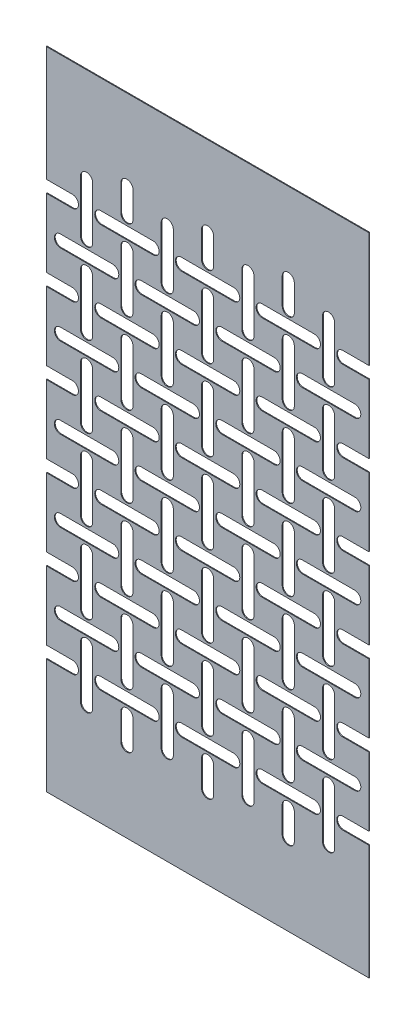
SolidWorks part; units mm, degrees
material "Kapton"
ref_plane "Front Plane" through (0, 0, 0) normal (0, 0, 1) x (1, 0, 0)
ref_plane "Top Plane" through (0, 0, 0) normal (0, 1, 0) x (1, 0, 0)
ref_plane "Right Plane" through (0, 0, 0) normal (1, 0, 0) x (0, 0, -1)
sketch "Model" plane through (0, 0, 0) normal (0, 0, 1) x (1, 0, 0)
  line L0 (0, 31.5) -> (6.4793, 31.5)
  line L1 (0, 28.5) -> (6.4793, 28.5)
  line L2 (13.5207, 31.5) -> (26.4793, 31.5)
  line L3 (13.5207, 28.5) -> (26.4793, 28.5)
  line L4 (33.5207, 31.5) -> (46.4793, 31.5)
  line L5 (33.5207, 28.5) -> (46.4793, 28.5)
  line L6 (53.5207, 31.5) -> (66.4793, 31.5)
  line L7 (53.5207, 28.5) -> (66.4793, 28.5)
  line L8 (73.5207, 31.5) -> (80, 31.5)
  line L9 (73.5207, 28.5) -> (80, 28.5)
  line L10 (3.5207, 41.5) -> (16.4793, 41.5)
  line L11 (3.5207, 38.5) -> (16.4793, 38.5)
  line L12 (23.5207, 41.5) -> (36.4793, 41.5)
  line L13 (23.5207, 38.5) -> (36.4793, 38.5)
  line L14 (43.5207, 41.5) -> (56.4793, 41.5)
  line L15 (43.5207, 38.5) -> (56.4793, 38.5)
  line L16 (63.5207, 41.5) -> (76.4793, 41.5)
  line L17 (63.5207, 38.5) -> (76.4793, 38.5)
  line L18 (0, 51.5) -> (6.4793, 51.5)
  line L19 (0, 48.5) -> (6.4793, 48.5)
  line L20 (13.5207, 51.5) -> (26.4793, 51.5)
  line L21 (13.5207, 48.5) -> (26.4793, 48.5)
  line L22 (33.5207, 51.5) -> (46.4793, 51.5)
  line L23 (33.5207, 48.5) -> (46.4793, 48.5)
  line L24 (53.5207, 51.5) -> (66.4793, 51.5)
  line L25 (53.5207, 48.5) -> (66.4793, 48.5)
  line L26 (73.5207, 51.5) -> (80, 51.5)
  line L27 (73.5207, 48.5) -> (80, 48.5)
  line L28 (3.5207, 61.5) -> (16.4793, 61.5)
  line L29 (3.5207, 58.5) -> (16.4793, 58.5)
  line L30 (23.5207, 61.5) -> (36.4793, 61.5)
  line L31 (23.5207, 58.5) -> (36.4793, 58.5)
  line L32 (43.5207, 61.5) -> (56.4793, 61.5)
  line L33 (43.5207, 58.5) -> (56.4793, 58.5)
  line L34 (63.5207, 61.5) -> (76.4793, 61.5)
  line L35 (63.5207, 58.5) -> (76.4793, 58.5)
  line L36 (0, 71.5) -> (6.4793, 71.5)
  line L37 (0, 68.5) -> (6.4793, 68.5)
  line L38 (13.5207, 71.5) -> (26.4793, 71.5)
  line L39 (13.5207, 68.5) -> (26.4793, 68.5)
  line L40 (33.5207, 71.5) -> (46.4793, 71.5)
  line L41 (33.5207, 68.5) -> (46.4793, 68.5)
  line L42 (53.5207, 71.5) -> (66.4793, 71.5)
  line L43 (53.5207, 68.5) -> (66.4793, 68.5)
  line L44 (73.5207, 71.5) -> (80, 71.5)
  line L45 (73.5207, 68.5) -> (80, 68.5)
  line L46 (3.5207, 81.5) -> (16.4793, 81.5)
  line L47 (3.5207, 78.5) -> (16.4793, 78.5)
  line L48 (23.5207, 81.5) -> (36.4793, 81.5)
  line L49 (23.5207, 78.5) -> (36.4793, 78.5)
  line L50 (43.5207, 81.5) -> (56.4793, 81.5)
  line L51 (43.5207, 78.5) -> (56.4793, 78.5)
  line L52 (63.5207, 81.5) -> (76.4793, 81.5)
  line L53 (63.5207, 78.5) -> (76.4793, 78.5)
  line L54 (0, 91.5) -> (6.4793, 91.5)
  line L55 (0, 88.5) -> (6.4793, 88.5)
  line L56 (13.5207, 91.5) -> (26.4793, 91.5)
  line L57 (13.5207, 88.5) -> (26.4793, 88.5)
  line L58 (33.5207, 91.5) -> (46.4793, 91.5)
  line L59 (33.5207, 88.5) -> (46.4793, 88.5)
  line L60 (53.5207, 91.5) -> (66.4793, 91.5)
  line L61 (53.5207, 88.5) -> (66.4793, 88.5)
  line L62 (73.5207, 91.5) -> (80, 91.5)
  line L63 (73.5207, 88.5) -> (80, 88.5)
  line L64 (3.5207, 101.5) -> (16.4793, 101.5)
  line L65 (3.5207, 98.5) -> (16.4793, 98.5)
  line L66 (23.5207, 101.5) -> (36.4793, 101.5)
  line L67 (23.5207, 98.5) -> (36.4793, 98.5)
  line L68 (43.5207, 101.5) -> (56.4793, 101.5)
  line L69 (43.5207, 98.5) -> (56.4793, 98.5)
  line L70 (63.5207, 101.5) -> (76.4793, 101.5)
  line L71 (63.5207, 98.5) -> (76.4793, 98.5)
  line L72 (0, 111.5) -> (6.4793, 111.5)
  line L73 (0, 108.5) -> (6.4793, 108.5)
  line L74 (13.5207, 111.5) -> (26.4793, 111.5)
  line L75 (13.5207, 108.5) -> (26.4793, 108.5)
  line L76 (33.5207, 111.5) -> (46.4793, 111.5)
  line L77 (33.5207, 108.5) -> (46.4793, 108.5)
  line L78 (53.5207, 111.5) -> (66.4793, 111.5)
  line L79 (53.5207, 108.5) -> (66.4793, 108.5)
  line L80 (73.5207, 111.5) -> (80, 111.5)
  line L81 (73.5207, 108.5) -> (80, 108.5)
  line L82 (3.5207, 121.5) -> (16.4793, 121.5)
  line L83 (3.5207, 118.5) -> (16.4793, 118.5)
  line L84 (23.5207, 121.5) -> (36.4793, 121.5)
  line L85 (23.5207, 118.5) -> (36.4793, 118.5)
  line L86 (43.5207, 121.5) -> (56.4793, 121.5)
  line L87 (43.5207, 118.5) -> (56.4793, 118.5)
  line L88 (63.5207, 121.5) -> (76.4793, 121.5)
  line L89 (63.5207, 118.5) -> (76.4793, 118.5)
  line L90 (0, 131.5) -> (6.4793, 131.5)
  line L91 (0, 128.5) -> (6.4793, 128.5)
  line L92 (13.5207, 131.5) -> (26.4793, 131.5)
  line L93 (13.5207, 128.5) -> (26.4793, 128.5)
  line L94 (33.5207, 131.5) -> (46.4793, 131.5)
  line L95 (33.5207, 128.5) -> (46.4793, 128.5)
  line L96 (53.5207, 131.5) -> (66.4793, 131.5)
  line L97 (53.5207, 128.5) -> (66.4793, 128.5)
  line L98 (73.5207, 131.5) -> (80, 131.5)
  line L99 (73.5207, 128.5) -> (80, 128.5)
  line L100 (11.5, 23.5207) -> (11.5, 36.4793)
  line L101 (8.5, 23.5207) -> (8.5, 36.4793)
  line L102 (11.5, 43.5207) -> (11.5, 56.4793)
  line L103 (8.5, 43.5207) -> (8.5, 56.4793)
  line L104 (11.5, 63.5207) -> (11.5, 76.4793)
  line L105 (8.5, 63.5207) -> (8.5, 76.4793)
  line L106 (11.5, 83.5207) -> (11.5, 96.4793)
  line L107 (8.5, 83.5207) -> (8.5, 96.4793)
  line L108 (11.5, 103.5207) -> (11.5, 116.4793)
  line L109 (8.5, 103.5207) -> (8.5, 116.4793)
  line L110 (11.5, 123.5207) -> (11.5, 136.4793)
  line L111 (8.5, 123.5207) -> (8.5, 136.4793)
  line L112 (21.5, 20) -> (21.5, 26.4793)
  line L113 (18.5, 20) -> (18.5, 26.4793)
  line L114 (21.5, 33.5207) -> (21.5, 46.4793)
  line L115 (18.5, 33.5207) -> (18.5, 46.4793)
  line L116 (21.5, 53.5207) -> (21.5, 66.4793)
  line L117 (18.5, 53.5207) -> (18.5, 66.4793)
  line L118 (21.5, 73.5207) -> (21.5, 86.4793)
  line L119 (18.5, 73.5207) -> (18.5, 86.4793)
  line L120 (21.5, 93.5207) -> (21.5, 106.4793)
  line L121 (18.5, 93.5207) -> (18.5, 106.4793)
  line L122 (21.5, 113.5207) -> (21.5, 126.4793)
  line L123 (18.5, 113.5207) -> (18.5, 126.4793)
  line L124 (21.5, 133.5207) -> (21.5, 140)
  line L125 (18.5, 133.5207) -> (18.5, 140)
  line L126 (31.5, 23.5207) -> (31.5, 36.4793)
  line L127 (28.5, 23.5207) -> (28.5, 36.4793)
  line L128 (31.5, 43.5207) -> (31.5, 56.4793)
  line L129 (28.5, 43.5207) -> (28.5, 56.4793)
  line L130 (31.5, 63.5207) -> (31.5, 76.4793)
  line L131 (28.5, 63.5207) -> (28.5, 76.4793)
  line L132 (31.5, 83.5207) -> (31.5, 96.4793)
  line L133 (28.5, 83.5207) -> (28.5, 96.4793)
  line L134 (31.5, 103.5207) -> (31.5, 116.4793)
  line L135 (28.5, 103.5207) -> (28.5, 116.4793)
  line L136 (31.5, 123.5207) -> (31.5, 136.4793)
  line L137 (28.5, 123.5207) -> (28.5, 136.4793)
  line L138 (41.5, 20) -> (41.5, 26.4793)
  line L139 (38.5, 20) -> (38.5, 26.4793)
  line L140 (41.5, 33.5207) -> (41.5, 46.4793)
  line L141 (38.5, 33.5207) -> (38.5, 46.4793)
  line L142 (41.5, 53.5207) -> (41.5, 66.4793)
  line L143 (38.5, 53.5207) -> (38.5, 66.4793)
  line L144 (41.5, 73.5207) -> (41.5, 86.4793)
  line L145 (38.5, 73.5207) -> (38.5, 86.4793)
  line L146 (41.5, 93.5207) -> (41.5, 106.4793)
  line L147 (38.5, 93.5207) -> (38.5, 106.4793)
  line L148 (41.5, 113.5207) -> (41.5, 126.4793)
  line L149 (38.5, 113.5207) -> (38.5, 126.4793)
  line L150 (41.5, 133.5207) -> (41.5, 140)
  line L151 (38.5, 133.5207) -> (38.5, 140)
  line L152 (51.5, 23.5207) -> (51.5, 36.4793)
  line L153 (48.5, 23.5207) -> (48.5, 36.4793)
  line L154 (51.5, 43.5207) -> (51.5, 56.4793)
  line L155 (48.5, 43.5207) -> (48.5, 56.4793)
  line L156 (51.5, 63.5207) -> (51.5, 76.4793)
  line L157 (48.5, 63.5207) -> (48.5, 76.4793)
  line L158 (51.5, 83.5207) -> (51.5, 96.4793)
  line L159 (48.5, 83.5207) -> (48.5, 96.4793)
  line L160 (51.5, 103.5207) -> (51.5, 116.4793)
  line L161 (48.5, 103.5207) -> (48.5, 116.4793)
  line L162 (51.5, 123.5207) -> (51.5, 136.4793)
  line L163 (48.5, 123.5207) -> (48.5, 136.4793)
  line L164 (61.5, 20) -> (61.5, 26.4793)
  line L165 (58.5, 20) -> (58.5, 26.4793)
  line L166 (61.5, 33.5207) -> (61.5, 46.4793)
  line L167 (58.5, 33.5207) -> (58.5, 46.4793)
  line L168 (61.5, 53.5207) -> (61.5, 66.4793)
  line L169 (58.5, 53.5207) -> (58.5, 66.4793)
  line L170 (61.5, 73.5207) -> (61.5, 86.4793)
  line L171 (58.5, 73.5207) -> (58.5, 86.4793)
  line L172 (61.5, 93.5207) -> (61.5, 106.4793)
  line L173 (58.5, 93.5207) -> (58.5, 106.4793)
  line L174 (61.5, 113.5207) -> (61.5, 126.4793)
  line L175 (58.5, 113.5207) -> (58.5, 126.4793)
  line L176 (61.5, 133.5207) -> (61.5, 140)
  line L177 (58.5, 133.5207) -> (58.5, 140)
  line L178 (71.5, 23.5207) -> (71.5, 36.4793)
  line L179 (68.5, 23.5207) -> (68.5, 36.4793)
  line L180 (71.5, 43.5207) -> (71.5, 56.4793)
  line L181 (68.5, 43.5207) -> (68.5, 56.4793)
  line L182 (71.5, 63.5207) -> (71.5, 76.4793)
  line L183 (68.5, 63.5207) -> (68.5, 76.4793)
  line L184 (71.5, 83.5207) -> (71.5, 96.4793)
  line L185 (68.5, 83.5207) -> (68.5, 96.4793)
  line L186 (71.5, 103.5207) -> (71.5, 116.4793)
  line L187 (68.5, 103.5207) -> (68.5, 116.4793)
  line L188 (71.5, 123.5207) -> (71.5, 136.4793)
  line L189 (68.5, 123.5207) -> (68.5, 136.4793)
  line L190 (0, 0) -> (80, 0)
  line L191 (80, 0) -> (80, 28.5)
  line L192 (80, 31.5) -> (80, 48.5)
  line L193 (80, 51.5) -> (80, 68.5)
  line L194 (80, 71.5) -> (80, 88.5)
  line L195 (80, 91.5) -> (80, 108.5)
  line L196 (80, 111.5) -> (80, 128.5)
  line L197 (80, 131.5) -> (80, 160)
  line L198 (80, 160) -> (0, 160)
  line L199 (0, 0) -> (0, 28.5)
  line L200 (0, 31.5) -> (0, 48.5)
  line L201 (0, 51.5) -> (0, 68.5)
  line L202 (0, 71.5) -> (0, 88.5)
  line L203 (0, 91.5) -> (0, 108.5)
  line L204 (0, 111.5) -> (0, 128.5)
  line L205 (0, 131.5) -> (0, 160)
  arc A0 (6.4793, 28.5) -> (6.4793, 31.5) centre (6.4793, 30) ccw
  arc A1 (13.5207, 31.5) -> (13.5207, 28.5) centre (13.5207, 30) ccw
  arc A2 (26.4793, 28.5) -> (26.4793, 31.5) centre (26.4793, 30) ccw
  arc A3 (33.5207, 31.5) -> (33.5207, 28.5) centre (33.5207, 30) ccw
  arc A4 (46.4793, 28.5) -> (46.4793, 31.5) centre (46.4793, 30) ccw
  arc A5 (53.5207, 31.5) -> (53.5207, 28.5) centre (53.5207, 30) ccw
  arc A6 (66.4793, 28.5) -> (66.4793, 31.5) centre (66.4793, 30) ccw
  arc A7 (73.5207, 31.5) -> (73.5207, 28.5) centre (73.5207, 30) ccw
  arc A8 (3.5207, 41.5) -> (3.5207, 38.5) centre (3.5207, 40) ccw
  arc A9 (16.4793, 38.5) -> (16.4793, 41.5) centre (16.4793, 40) ccw
  arc A10 (23.5207, 41.5) -> (23.5207, 38.5) centre (23.5207, 40) ccw
  arc A11 (36.4793, 38.5) -> (36.4793, 41.5) centre (36.4793, 40) ccw
  arc A12 (43.5207, 41.5) -> (43.5207, 38.5) centre (43.5207, 40) ccw
  arc A13 (56.4793, 38.5) -> (56.4793, 41.5) centre (56.4793, 40) ccw
  arc A14 (63.5207, 41.5) -> (63.5207, 38.5) centre (63.5207, 40) ccw
  arc A15 (76.4793, 38.5) -> (76.4793, 41.5) centre (76.4793, 40) ccw
  arc A16 (6.4793, 48.5) -> (6.4793, 51.5) centre (6.4793, 50) ccw
  arc A17 (13.5207, 51.5) -> (13.5207, 48.5) centre (13.5207, 50) ccw
  arc A18 (26.4793, 48.5) -> (26.4793, 51.5) centre (26.4793, 50) ccw
  arc A19 (33.5207, 51.5) -> (33.5207, 48.5) centre (33.5207, 50) ccw
  arc A20 (46.4793, 48.5) -> (46.4793, 51.5) centre (46.4793, 50) ccw
  arc A21 (53.5207, 51.5) -> (53.5207, 48.5) centre (53.5207, 50) ccw
  arc A22 (66.4793, 48.5) -> (66.4793, 51.5) centre (66.4793, 50) ccw
  arc A23 (73.5207, 51.5) -> (73.5207, 48.5) centre (73.5207, 50) ccw
  arc A24 (3.5207, 61.5) -> (3.5207, 58.5) centre (3.5207, 60) ccw
  arc A25 (16.4793, 58.5) -> (16.4793, 61.5) centre (16.4793, 60) ccw
  arc A26 (23.5207, 61.5) -> (23.5207, 58.5) centre (23.5207, 60) ccw
  arc A27 (36.4793, 58.5) -> (36.4793, 61.5) centre (36.4793, 60) ccw
  arc A28 (43.5207, 61.5) -> (43.5207, 58.5) centre (43.5207, 60) ccw
  arc A29 (56.4793, 58.5) -> (56.4793, 61.5) centre (56.4793, 60) ccw
  arc A30 (63.5207, 61.5) -> (63.5207, 58.5) centre (63.5207, 60) ccw
  arc A31 (76.4793, 58.5) -> (76.4793, 61.5) centre (76.4793, 60) ccw
  arc A32 (6.4793, 68.5) -> (6.4793, 71.5) centre (6.4793, 70) ccw
  arc A33 (13.5207, 71.5) -> (13.5207, 68.5) centre (13.5207, 70) ccw
  arc A34 (26.4793, 68.5) -> (26.4793, 71.5) centre (26.4793, 70) ccw
  arc A35 (33.5207, 71.5) -> (33.5207, 68.5) centre (33.5207, 70) ccw
  arc A36 (46.4793, 68.5) -> (46.4793, 71.5) centre (46.4793, 70) ccw
  arc A37 (53.5207, 71.5) -> (53.5207, 68.5) centre (53.5207, 70) ccw
  arc A38 (66.4793, 68.5) -> (66.4793, 71.5) centre (66.4793, 70) ccw
  arc A39 (73.5207, 71.5) -> (73.5207, 68.5) centre (73.5207, 70) ccw
  arc A40 (3.5207, 81.5) -> (3.5207, 78.5) centre (3.5207, 80) ccw
  arc A41 (16.4793, 78.5) -> (16.4793, 81.5) centre (16.4793, 80) ccw
  arc A42 (23.5207, 81.5) -> (23.5207, 78.5) centre (23.5207, 80) ccw
  arc A43 (36.4793, 78.5) -> (36.4793, 81.5) centre (36.4793, 80) ccw
  arc A44 (43.5207, 81.5) -> (43.5207, 78.5) centre (43.5207, 80) ccw
  arc A45 (56.4793, 78.5) -> (56.4793, 81.5) centre (56.4793, 80) ccw
  arc A46 (63.5207, 81.5) -> (63.5207, 78.5) centre (63.5207, 80) ccw
  arc A47 (76.4793, 78.5) -> (76.4793, 81.5) centre (76.4793, 80) ccw
  arc A48 (6.4793, 88.5) -> (6.4793, 91.5) centre (6.4793, 90) ccw
  arc A49 (13.5207, 91.5) -> (13.5207, 88.5) centre (13.5207, 90) ccw
  arc A50 (26.4793, 88.5) -> (26.4793, 91.5) centre (26.4793, 90) ccw
  arc A51 (33.5207, 91.5) -> (33.5207, 88.5) centre (33.5207, 90) ccw
  arc A52 (46.4793, 88.5) -> (46.4793, 91.5) centre (46.4793, 90) ccw
  arc A53 (53.5207, 91.5) -> (53.5207, 88.5) centre (53.5207, 90) ccw
  arc A54 (66.4793, 88.5) -> (66.4793, 91.5) centre (66.4793, 90) ccw
  arc A55 (73.5207, 91.5) -> (73.5207, 88.5) centre (73.5207, 90) ccw
  arc A56 (3.5207, 101.5) -> (3.5207, 98.5) centre (3.5207, 100) ccw
  arc A57 (16.4793, 98.5) -> (16.4793, 101.5) centre (16.4793, 100) ccw
  arc A58 (23.5207, 101.5) -> (23.5207, 98.5) centre (23.5207, 100) ccw
  arc A59 (36.4793, 98.5) -> (36.4793, 101.5) centre (36.4793, 100) ccw
  arc A60 (43.5207, 101.5) -> (43.5207, 98.5) centre (43.5207, 100) ccw
  arc A61 (56.4793, 98.5) -> (56.4793, 101.5) centre (56.4793, 100) ccw
  arc A62 (63.5207, 101.5) -> (63.5207, 98.5) centre (63.5207, 100) ccw
  arc A63 (76.4793, 98.5) -> (76.4793, 101.5) centre (76.4793, 100) ccw
  arc A64 (6.4793, 108.5) -> (6.4793, 111.5) centre (6.4793, 110) ccw
  arc A65 (13.5207, 111.5) -> (13.5207, 108.5) centre (13.5207, 110) ccw
  arc A66 (26.4793, 108.5) -> (26.4793, 111.5) centre (26.4793, 110) ccw
  arc A67 (33.5207, 111.5) -> (33.5207, 108.5) centre (33.5207, 110) ccw
  arc A68 (46.4793, 108.5) -> (46.4793, 111.5) centre (46.4793, 110) ccw
  arc A69 (53.5207, 111.5) -> (53.5207, 108.5) centre (53.5207, 110) ccw
  arc A70 (66.4793, 108.5) -> (66.4793, 111.5) centre (66.4793, 110) ccw
  arc A71 (73.5207, 111.5) -> (73.5207, 108.5) centre (73.5207, 110) ccw
  arc A72 (3.5207, 121.5) -> (3.5207, 118.5) centre (3.5207, 120) ccw
  arc A73 (16.4793, 118.5) -> (16.4793, 121.5) centre (16.4793, 120) ccw
  arc A74 (23.5207, 121.5) -> (23.5207, 118.5) centre (23.5207, 120) ccw
  arc A75 (36.4793, 118.5) -> (36.4793, 121.5) centre (36.4793, 120) ccw
  arc A76 (43.5207, 121.5) -> (43.5207, 118.5) centre (43.5207, 120) ccw
  arc A77 (56.4793, 118.5) -> (56.4793, 121.5) centre (56.4793, 120) ccw
  arc A78 (63.5207, 121.5) -> (63.5207, 118.5) centre (63.5207, 120) ccw
  arc A79 (76.4793, 118.5) -> (76.4793, 121.5) centre (76.4793, 120) ccw
  arc A80 (6.4793, 128.5) -> (6.4793, 131.5) centre (6.4793, 130) ccw
  arc A81 (13.5207, 131.5) -> (13.5207, 128.5) centre (13.5207, 130) ccw
  arc A82 (26.4793, 128.5) -> (26.4793, 131.5) centre (26.4793, 130) ccw
  arc A83 (33.5207, 131.5) -> (33.5207, 128.5) centre (33.5207, 130) ccw
  arc A84 (46.4793, 128.5) -> (46.4793, 131.5) centre (46.4793, 130) ccw
  arc A85 (53.5207, 131.5) -> (53.5207, 128.5) centre (53.5207, 130) ccw
  arc A86 (66.4793, 128.5) -> (66.4793, 131.5) centre (66.4793, 130) ccw
  arc A87 (73.5207, 131.5) -> (73.5207, 128.5) centre (73.5207, 130) ccw
  arc A88 (8.5, 23.5207) -> (11.5, 23.5207) centre (10, 23.5207) ccw
  arc A89 (11.5, 36.4793) -> (8.5, 36.4793) centre (10, 36.4793) ccw
  arc A90 (8.5, 43.5207) -> (11.5, 43.5207) centre (10, 43.5207) ccw
  arc A91 (11.5, 56.4793) -> (8.5, 56.4793) centre (10, 56.4793) ccw
  arc A92 (8.5, 63.5207) -> (11.5, 63.5207) centre (10, 63.5207) ccw
  arc A93 (11.5, 76.4793) -> (8.5, 76.4793) centre (10, 76.4793) ccw
  arc A94 (8.5, 83.5207) -> (11.5, 83.5207) centre (10, 83.5207) ccw
  arc A95 (11.5, 96.4793) -> (8.5, 96.4793) centre (10, 96.4793) ccw
  arc A96 (8.5, 103.5207) -> (11.5, 103.5207) centre (10, 103.5207) ccw
  arc A97 (11.5, 116.4793) -> (8.5, 116.4793) centre (10, 116.4793) ccw
  arc A98 (8.5, 123.5207) -> (11.5, 123.5207) centre (10, 123.5207) ccw
  arc A99 (11.5, 136.4793) -> (8.5, 136.4793) centre (10, 136.4793) ccw
  arc A100 (18.5, 20) -> (21.5, 20) centre (20, 20) ccw
  arc A101 (21.5, 26.4793) -> (18.5, 26.4793) centre (20, 26.4793) ccw
  arc A102 (18.5, 33.5207) -> (21.5, 33.5207) centre (20, 33.5207) ccw
  arc A103 (21.5, 46.4793) -> (18.5, 46.4793) centre (20, 46.4793) ccw
  arc A104 (18.5, 53.5207) -> (21.5, 53.5207) centre (20, 53.5207) ccw
  arc A105 (21.5, 66.4793) -> (18.5, 66.4793) centre (20, 66.4793) ccw
  arc A106 (18.5, 73.5207) -> (21.5, 73.5207) centre (20, 73.5207) ccw
  arc A107 (21.5, 86.4793) -> (18.5, 86.4793) centre (20, 86.4793) ccw
  arc A108 (18.5, 93.5207) -> (21.5, 93.5207) centre (20, 93.5207) ccw
  arc A109 (21.5, 106.4793) -> (18.5, 106.4793) centre (20, 106.4793) ccw
  arc A110 (18.5, 113.5207) -> (21.5, 113.5207) centre (20, 113.5207) ccw
  arc A111 (21.5, 126.4793) -> (18.5, 126.4793) centre (20, 126.4793) ccw
  arc A112 (18.5, 133.5207) -> (21.5, 133.5207) centre (20, 133.5207) ccw
  arc A113 (21.5, 140) -> (18.5, 140) centre (20, 140) ccw
  arc A114 (28.5, 23.5207) -> (31.5, 23.5207) centre (30, 23.5207) ccw
  arc A115 (31.5, 36.4793) -> (28.5, 36.4793) centre (30, 36.4793) ccw
  arc A116 (28.5, 43.5207) -> (31.5, 43.5207) centre (30, 43.5207) ccw
  arc A117 (31.5, 56.4793) -> (28.5, 56.4793) centre (30, 56.4793) ccw
  arc A118 (28.5, 63.5207) -> (31.5, 63.5207) centre (30, 63.5207) ccw
  arc A119 (31.5, 76.4793) -> (28.5, 76.4793) centre (30, 76.4793) ccw
  arc A120 (28.5, 83.5207) -> (31.5, 83.5207) centre (30, 83.5207) ccw
  arc A121 (31.5, 96.4793) -> (28.5, 96.4793) centre (30, 96.4793) ccw
  arc A122 (28.5, 103.5207) -> (31.5, 103.5207) centre (30, 103.5207) ccw
  arc A123 (31.5, 116.4793) -> (28.5, 116.4793) centre (30, 116.4793) ccw
  arc A124 (28.5, 123.5207) -> (31.5, 123.5207) centre (30, 123.5207) ccw
  arc A125 (31.5, 136.4793) -> (28.5, 136.4793) centre (30, 136.4793) ccw
  arc A126 (38.5, 20) -> (41.5, 20) centre (40, 20) ccw
  arc A127 (41.5, 26.4793) -> (38.5, 26.4793) centre (40, 26.4793) ccw
  arc A128 (38.5, 33.5207) -> (41.5, 33.5207) centre (40, 33.5207) ccw
  arc A129 (41.5, 46.4793) -> (38.5, 46.4793) centre (40, 46.4793) ccw
  arc A130 (38.5, 53.5207) -> (41.5, 53.5207) centre (40, 53.5207) ccw
  arc A131 (41.5, 66.4793) -> (38.5, 66.4793) centre (40, 66.4793) ccw
  arc A132 (38.5, 73.5207) -> (41.5, 73.5207) centre (40, 73.5207) ccw
  arc A133 (41.5, 86.4793) -> (38.5, 86.4793) centre (40, 86.4793) ccw
  arc A134 (38.5, 93.5207) -> (41.5, 93.5207) centre (40, 93.5207) ccw
  arc A135 (41.5, 106.4793) -> (38.5, 106.4793) centre (40, 106.4793) ccw
  arc A136 (38.5, 113.5207) -> (41.5, 113.5207) centre (40, 113.5207) ccw
  arc A137 (41.5, 126.4793) -> (38.5, 126.4793) centre (40, 126.4793) ccw
  arc A138 (38.5, 133.5207) -> (41.5, 133.5207) centre (40, 133.5207) ccw
  arc A139 (41.5, 140) -> (38.5, 140) centre (40, 140) ccw
  arc A140 (48.5, 23.5207) -> (51.5, 23.5207) centre (50, 23.5207) ccw
  arc A141 (51.5, 36.4793) -> (48.5, 36.4793) centre (50, 36.4793) ccw
  arc A142 (48.5, 43.5207) -> (51.5, 43.5207) centre (50, 43.5207) ccw
  arc A143 (51.5, 56.4793) -> (48.5, 56.4793) centre (50, 56.4793) ccw
  arc A144 (48.5, 63.5207) -> (51.5, 63.5207) centre (50, 63.5207) ccw
  arc A145 (51.5, 76.4793) -> (48.5, 76.4793) centre (50, 76.4793) ccw
  arc A146 (48.5, 83.5207) -> (51.5, 83.5207) centre (50, 83.5207) ccw
  arc A147 (51.5, 96.4793) -> (48.5, 96.4793) centre (50, 96.4793) ccw
  arc A148 (48.5, 103.5207) -> (51.5, 103.5207) centre (50, 103.5207) ccw
  arc A149 (51.5, 116.4793) -> (48.5, 116.4793) centre (50, 116.4793) ccw
  arc A150 (48.5, 123.5207) -> (51.5, 123.5207) centre (50, 123.5207) ccw
  arc A151 (51.5, 136.4793) -> (48.5, 136.4793) centre (50, 136.4793) ccw
  arc A152 (58.5, 20) -> (61.5, 20) centre (60, 20) ccw
  arc A153 (61.5, 26.4793) -> (58.5, 26.4793) centre (60, 26.4793) ccw
  arc A154 (58.5, 33.5207) -> (61.5, 33.5207) centre (60, 33.5207) ccw
  arc A155 (61.5, 46.4793) -> (58.5, 46.4793) centre (60, 46.4793) ccw
  arc A156 (58.5, 53.5207) -> (61.5, 53.5207) centre (60, 53.5207) ccw
  arc A157 (61.5, 66.4793) -> (58.5, 66.4793) centre (60, 66.4793) ccw
  arc A158 (58.5, 73.5207) -> (61.5, 73.5207) centre (60, 73.5207) ccw
  arc A159 (61.5, 86.4793) -> (58.5, 86.4793) centre (60, 86.4793) ccw
  arc A160 (58.5, 93.5207) -> (61.5, 93.5207) centre (60, 93.5207) ccw
  arc A161 (61.5, 106.4793) -> (58.5, 106.4793) centre (60, 106.4793) ccw
  arc A162 (58.5, 113.5207) -> (61.5, 113.5207) centre (60, 113.5207) ccw
  arc A163 (61.5, 126.4793) -> (58.5, 126.4793) centre (60, 126.4793) ccw
  arc A164 (58.5, 133.5207) -> (61.5, 133.5207) centre (60, 133.5207) ccw
  arc A165 (61.5, 140) -> (58.5, 140) centre (60, 140) ccw
  arc A166 (68.5, 23.5207) -> (71.5, 23.5207) centre (70, 23.5207) ccw
  arc A167 (71.5, 36.4793) -> (68.5, 36.4793) centre (70, 36.4793) ccw
  arc A168 (68.5, 43.5207) -> (71.5, 43.5207) centre (70, 43.5207) ccw
  arc A169 (71.5, 56.4793) -> (68.5, 56.4793) centre (70, 56.4793) ccw
  arc A170 (68.5, 63.5207) -> (71.5, 63.5207) centre (70, 63.5207) ccw
  arc A171 (71.5, 76.4793) -> (68.5, 76.4793) centre (70, 76.4793) ccw
  arc A172 (68.5, 83.5207) -> (71.5, 83.5207) centre (70, 83.5207) ccw
  arc A173 (71.5, 96.4793) -> (68.5, 96.4793) centre (70, 96.4793) ccw
  arc A174 (68.5, 103.5207) -> (71.5, 103.5207) centre (70, 103.5207) ccw
  arc A175 (71.5, 116.4793) -> (68.5, 116.4793) centre (70, 116.4793) ccw
  arc A176 (68.5, 123.5207) -> (71.5, 123.5207) centre (70, 123.5207) ccw
  arc A177 (71.5, 136.4793) -> (68.5, 136.4793) centre (70, 136.4793) ccw
extrude "Boss-Extrude1" add sketch "Model" along normal blind 0.2
